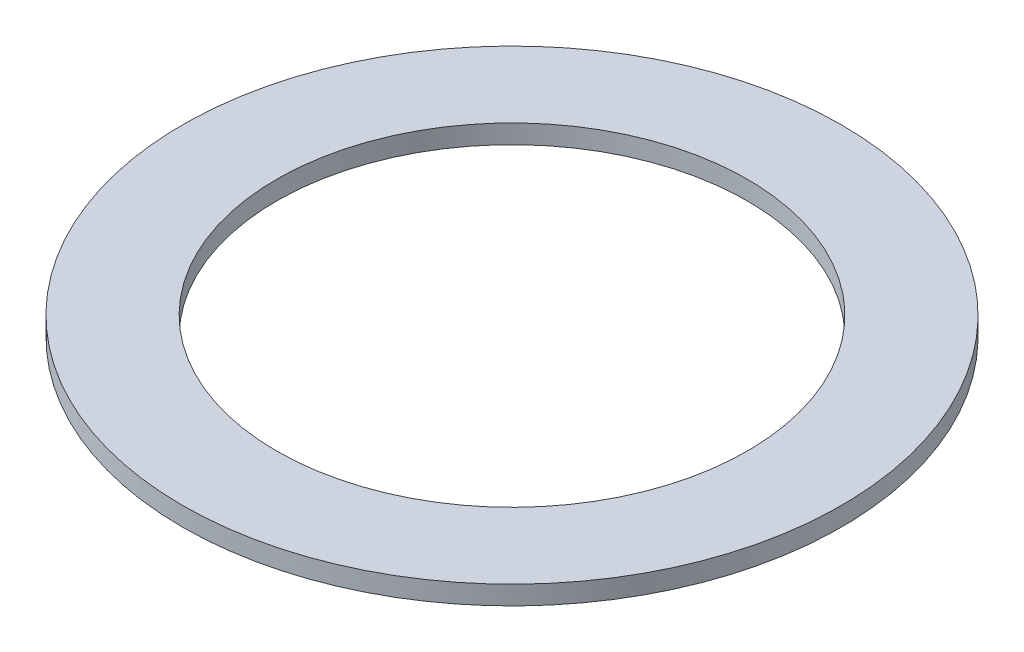
SolidWorks part; units mm, degrees
ref_plane "Piano frontale" through (0, 0, 0) normal (0, 0, 1) x (1, 0, 0)
ref_plane "Piano superiore" through (0, 0, 0) normal (0, 1, 0) x (1, 0, 0)
ref_plane "Piano destro" through (0, 0, 0) normal (1, 0, 0) x (0, 0, -1)
sketch "Schizzo1" plane through (0, 0, 0) normal (0, 1, 0) x (1, 0, 0)
  circle A0 centre (0, 0) radius 25
  circle A1 centre (0, 0) radius 35
  dimension "D1" = 50
  dimension "D2" = 70
extrude "Estrusione-Estrusione1" add sketch "Schizzo1" along normal blind 2 contours A1 | A0
